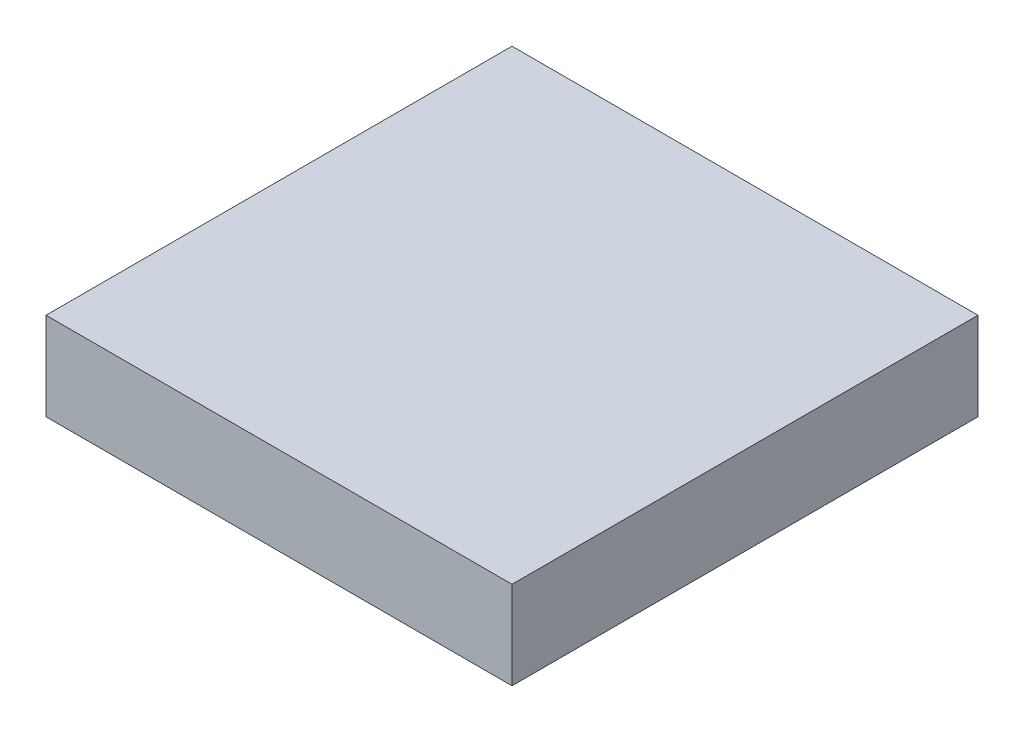
SolidWorks part; units mm, degrees
ref_plane "Front Plane" through (0, 0, 0) normal (0, 0, 1) x (1, 0, 0)
ref_plane "Top Plane" through (0, 0, 0) normal (0, 1, 0) x (1, 0, 0)
ref_plane "Right Plane" through (0, 0, 0) normal (1, 0, 0) x (0, 0, -1)
sketch "Sketch1" plane through (0, 0, 0) normal (0, 1, 0) x (1, 0, 0)
  line L1 (-28.2074, 45.406) -> (24.7926, 45.406)
  line L2 (-28.2074, 45.406) -> (-28.2074, -7.594)
  line L3 (-28.2074, -7.594) -> (24.7926, -7.594)
  line L4 (24.7926, 45.406) -> (24.7926, -7.594)
  dimension "D1" = 53
  dimension "D2" = 53
extrude "Boss-Extrude1" add sketch "Sketch1" along normal blind 10
